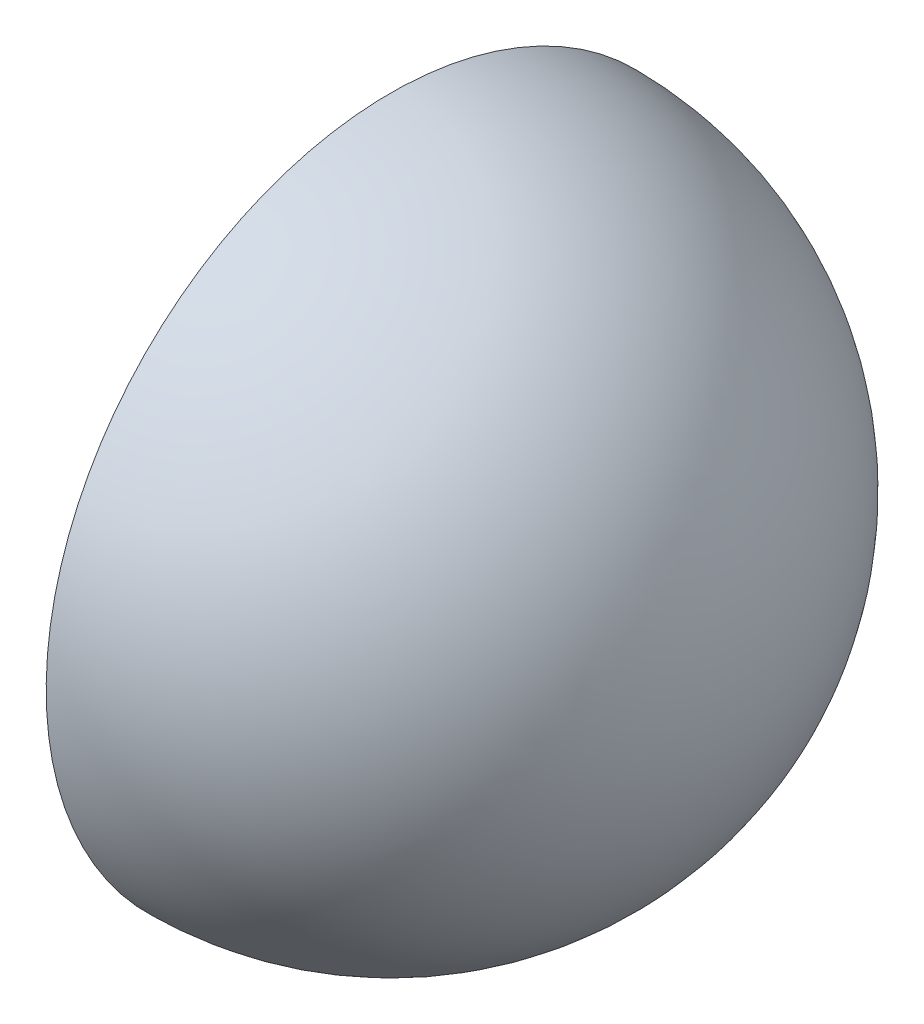
SolidWorks part; units mm, degrees
ref_plane "Front Plane" through (0, 0, 0) normal (0, 0, 1) x (1, 0, 0)
ref_plane "Top Plane" through (0, 0, 0) normal (0, 1, 0) x (1, 0, 0)
ref_plane "Right Plane" through (0, 0, 0) normal (1, 0, 0) x (0, 0, -1)
sketch "Sketch1" plane through (0, 0, 0) normal (0, 0, 1) x (1, 0, 0)
  line L0 (189.317, 0) -> (267.317, 0) construction
  line L2 (189.317, -75) -> (189.317, -78)
  line L3 (264.317, 0) -> (267.317, 0)
  arc A0 (189.317, -78) -> (267.317, 0) centre (189.317, 0) ccw
  arc A1 (189.317, -75) -> (264.317, 0) centre (189.317, 0) ccw
  dimension "D1" = 3
revolve "Revolve1" add sketch "Sketch1" angle 360 about L0
